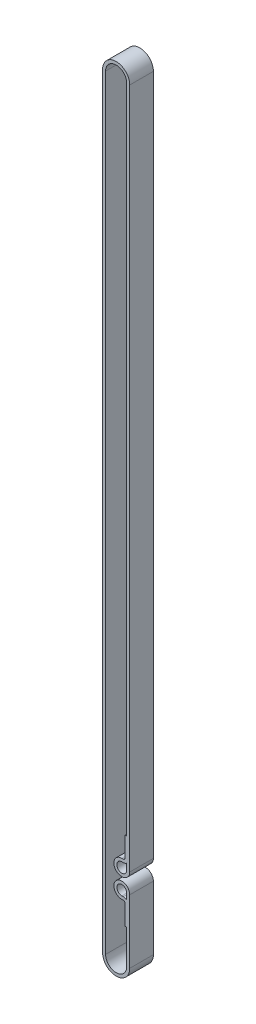
SolidWorks part; units mm, degrees
ref_plane "Front Plane" through (0, 0, 0) normal (0, 0, 1) x (1, 0, 0)
ref_plane "Top Plane" through (0, 0, 0) normal (0, 1, 0) x (1, 0, 0)
ref_plane "Right Plane" through (0, 0, 0) normal (1, 0, 0) x (0, 0, -1)
sketch "Sketch1" plane through (0, 0, 0) normal (0, 0, 1) x (1, 0, 0)
  line L0 (-6.365, 0) -> (-6.365, -388)
  line L1 (6.365, -388) -> (6.365, -355.7)
  line L2 (5.107, -370.704) -> (5.107, -360.704)
  line L3 (2.861, -345.7) -> (2.861, -355.7) construction
  line L4 (6.365, -345.7) -> (6.365, 0)
  line L5 (2.861, -359.204) -> (3.607, -359.204)
  line L6 (-997.139, -350.7) -> (49002.861, -350.7) construction
  line L7 (5.107, -330.696) -> (5.107, -340.696)
  line L8 (2.861, -342.196) -> (3.607, -342.196)
  arc A0 (6.365, 0) -> (-6.365, 0) centre (0, 0) ccw
  arc A1 (-6.365, -388) -> (6.365, -388) centre (0, -388) ccw
  circle A2 centre (2.861, -355.7) radius 2.5 construction
  arc A3 (6.365, -355.7) -> (2.861, -359.204) centre (2.861, -355.7) ccw
  arc A4 (3.607, -359.204) -> (5.107, -360.704) centre (3.607, -360.704) cw
  circle A5 centre (2.861, -345.7) radius 2.5 construction
  arc A6 (3.607, -342.196) -> (5.107, -340.696) centre (3.607, -340.696) ccw
  arc A7 (6.365, -345.7) -> (2.861, -342.196) centre (2.861, -345.7) cw
  point P11 (5.361, -355.7)
  point P22 (2.861, -350.7)
  dimension "D1" = 12.73
  dimension "D3" = 5
  dimension "D7" = 1.5
  dimension "D2" = 388
  dimension "D4" = 32.3
  dimension "D5" = 1.004
  dimension "D6" = 1.258
  dimension "D8" = 10
  dimension "D10" = 10
extrude "Extrude-Thin1" add sketch "Sketch1" along normal blind 12 thin
sketch "Sketch3" plane through (0, 0, 12) normal (0, 0, 1) x (1, 0, 0)
  line L11 (5.361, -355.7) -> (5.361, -358.917)
  line L12 (3.607, -358.2) -> (2.861, -358.2)
  line L13 (5.361, -355.7) -> (5.361, -358.917)
  line L14 (2.861, -343.2) -> (3.607, -343.2)
  line L15 (5.361, -342.483) -> (5.361, -345.7)
  line L16 (2.861, -343.2) -> (3.607, -343.2)
  line L17 (5.361, -342.483) -> (5.361, -345.7)
  line L18 (3.607, -358.2) -> (2.861, -358.2)
  line L20 (5.107, -340.696) -> (5.107, -330.696) construction
  line L21 (2.861, -342.196) -> (3.607, -342.196) construction
  line L22 (6.365, 0) -> (6.365, -345.7) construction
  line L23 (5.361, 0) -> (5.361, -345.7)
  line L24 (-5.361, -388) -> (-5.361, 0)
  line L25 (5.361, -355.7) -> (5.361, -388)
  line L26 (5.361, 0) -> (5.361, -330.696)
  line L27 (-5.361, -388) -> (-5.361, 0)
  line L28 (5.361, -355.7) -> (5.361, -358.917)
  line L29 (-6.365, -388) -> (-6.365, 0) construction
  line L30 (5.107, -370.704) -> (5.107, -360.704) construction
  line L31 (3.607, -359.204) -> (2.861, -359.204) construction
  line L32 (6.365, -355.7) -> (6.365, -388) construction
  line L33 (5.107, -340.696) -> (5.107, -330.696)
  line L34 (2.861, -342.196) -> (3.607, -342.196)
  line L35 (6.365, 0) -> (6.365, -345.7)
  line L36 (-6.365, -388) -> (-6.365, 0)
  line L37 (5.107, -370.704) -> (5.107, -360.704)
  line L38 (3.607, -359.204) -> (2.861, -359.204)
  line L39 (6.365, -355.7) -> (6.365, -388)
  line L40 (5.107, -330.696) -> (5.361, -330.696)
  line L41 (5.361, -342.483) -> (5.361, -345.7)
  line L42 (5.107, -370.704) -> (5.361, -370.704)
  line L43 (5.361, -370.704) -> (5.361, -388)
  arc A10 (5.361, -358.917) -> (3.607, -358.2) centre (3.607, -360.704) ccw
  arc A11 (5.361, -355.7) -> (2.861, -358.2) centre (2.861, -355.7) ccw
  arc A12 (3.607, -343.2) -> (5.361, -342.483) centre (3.607, -340.696) ccw
  arc A13 (2.861, -343.2) -> (5.361, -345.7) centre (2.861, -345.7) ccw
  arc A14 (3.607, -343.2) -> (5.361, -342.483) centre (3.607, -340.696) ccw
  arc A15 (2.861, -343.2) -> (5.361, -345.7) centre (2.861, -345.7) ccw
  arc A16 (5.361, -358.917) -> (3.607, -358.2) centre (3.607, -360.704) ccw
  arc A17 (5.361, -355.7) -> (2.861, -358.2) centre (2.861, -355.7) ccw
  arc A18 (3.607, -342.196) -> (5.107, -340.696) centre (3.607, -340.696) ccw construction
  arc A19 (2.861, -342.196) -> (6.365, -345.7) centre (2.861, -345.7) ccw construction
  arc A20 (5.361, 0) -> (-5.361, 0) centre (0, 0) ccw
  arc A21 (-5.361, -388) -> (5.361, -388) centre (0, -388) ccw
  arc A22 (5.361, 0) -> (-5.361, 0) centre (0, 0) ccw
  arc A23 (-5.361, -388) -> (5.361, -388) centre (0, -388) ccw
  arc A24 (6.365, 0) -> (-6.365, 0) centre (0, 0) ccw construction
  arc A25 (-6.365, -388) -> (6.365, -388) centre (0, -388) ccw construction
  arc A26 (5.107, -360.704) -> (3.607, -359.204) centre (3.607, -360.704) ccw construction
  arc A27 (6.365, -355.7) -> (2.861, -359.204) centre (2.861, -355.7) ccw construction
  arc A28 (3.607, -342.196) -> (5.107, -340.696) centre (3.607, -340.696) ccw
  arc A29 (2.861, -342.196) -> (6.365, -345.7) centre (2.861, -345.7) ccw
  arc A30 (6.365, 0) -> (-6.365, 0) centre (0, 0) ccw
  arc A31 (-6.365, -388) -> (6.365, -388) centre (0, -388) ccw
  arc A32 (5.107, -360.704) -> (3.607, -359.204) centre (3.607, -360.704) ccw
  arc A33 (6.365, -355.7) -> (2.861, -359.204) centre (2.861, -355.7) ccw
  line M14 (5.107, -340.696) -> (5.107, -330.696)
  line M30 (5.107, -370.704) -> (5.107, -360.704)
  arc M31 (5.107, -360.704) -> (3.607, -359.204) centre (3.607, -360.704) ccw
  line M32 (3.607, -359.204) -> (2.861, -359.204)
  arc M33 (2.861, -359.204) -> (6.365, -355.7) centre (2.861, -355.7) cw
  line M34 (6.365, -355.7) -> (6.365, -388)
  arc M35 (6.365, -388) -> (-6.365, -388) centre (0, -388) cw
  line M36 (-6.365, -388) -> (-6.365, 0)
  arc M37 (-6.365, 0) -> (6.365, 0) centre (0, 0) cw
  line M38 (6.365, 0) -> (6.365, -345.7)
  arc M39 (6.365, -345.7) -> (2.861, -342.196) centre (2.861, -345.7) cw
  line M40 (2.861, -342.196) -> (3.607, -342.196)
  arc M41 (3.607, -342.196) -> (5.107, -340.696) centre (3.607, -340.696) ccw
  dimension "D1" = 1.004
  dimension "D2" = 1.004
  dimension "D3" = 1.004
extrude "Boss-Extrude2" add sketch "Sketch3" against normal up to surface (12 mm away) contours A23 L27 A22 L26 L40 L42 L43 A17 L13 A16 L18 A15 L16 A14 L17 M14 M41 M40 M39 M38 M37 M36 M35 M34 M33 M32 M31 M30 up to face at (2.6436, -305.9286, 0)
